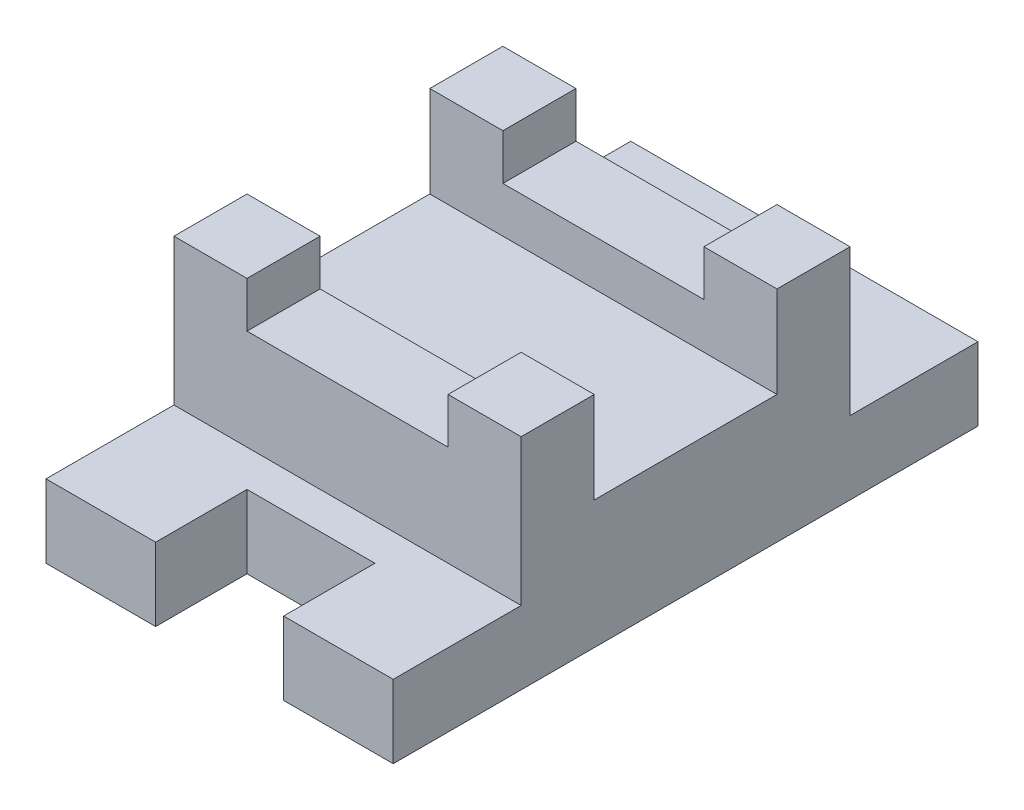
SolidWorks part; units mm, degrees
ref_plane "Front Plane" through (0, 0, 0) normal (0, 0, 1) x (1, 0, 0)
ref_plane "Top Plane" through (0, 0, 0) normal (0, 1, 0) x (1, 0, 0)
ref_plane "Right Plane" through (0, 0, 0) normal (1, 0, 0) x (0, 0, -1)
sketch "Sketch1" plane through (0, 0, 0) normal (1, 0, 0) x (0, 0, -1)
  line L0 (41.5, 10.375) -> (-22.5, 10.375)
  line L1 (-22.5, 10.375) -> (-22.5, 18.375)
  line L2 (-22.5, 18.375) -> (-8.5, 18.375)
  line L3 (-8.5, 18.375) -> (-8.5, 34.375)
  line L4 (-8.5, 34.375) -> (-0.5, 34.375)
  line L5 (-0.5, 34.375) -> (-0.5, 24.375)
  line L6 (-0.5, 24.375) -> (19.5, 24.375)
  line L7 (19.5, 24.375) -> (19.5, 34.375)
  line L8 (19.5, 34.375) -> (27.5, 34.375)
  line L9 (27.5, 34.375) -> (27.5, 18.375)
  line L10 (27.5, 18.375) -> (41.5, 18.375)
  line L11 (41.5, 18.375) -> (41.5, 10.375)
  dimension "D1" = 8
  dimension "D2" = 8
  dimension "D3" = 10
  dimension "D4" = 20
  dimension "D5" = 14
  dimension "D6" = 16
extrude "Boss-Extrude1" add sketch "Sketch1" along normal blind 38
sketch "Sketch2" plane through (0, 0, 8.5) normal (0, 0, 1) x (1, 0, 0)
  line L0 (38, 34.375) -> (0, 34.375) construction
  line L1 (30, 39.375) -> (8, 39.375)
  line L2 (30, 39.375) -> (30, 29.375)
  line L3 (30, 29.375) -> (8, 29.375)
  line L4 (8, 39.375) -> (8, 29.375)
  line L5 (30, 39.375) -> (8, 29.375) construction
  line L6 (30, 29.375) -> (8, 39.375) construction
  point P0 (19, 34.375)
  dimension "D1" = 22
  dimension "D2" = 10
extrude "Cut-Extrude1" cut sketch "Sketch2" against normal through all
sketch "Sketch3" plane through (0, 18.375, 0) normal (0, 1, 0) x (1, 0, 0)
  line L0 (38, -22.5) -> (0, -22.5) construction
  line L1 (12, -32.5) -> (26, -32.5)
  line L2 (12, -32.5) -> (12, -12.5)
  line L3 (12, -12.5) -> (26, -12.5)
  line L4 (26, -32.5) -> (26, -12.5)
  line L5 (12, -32.5) -> (26, -12.5) construction
  line L6 (12, -12.5) -> (26, -32.5) construction
  point P0 (19, -22.5)
  dimension "D1" = 14
  dimension "D2" = 20
extrude "Cut-Extrude2" cut sketch "Sketch3" against normal through all
ref_plane "Plane8" through (8, 29.375, 8.5) normal (0, 1, 0) x (1, 0, 0)
